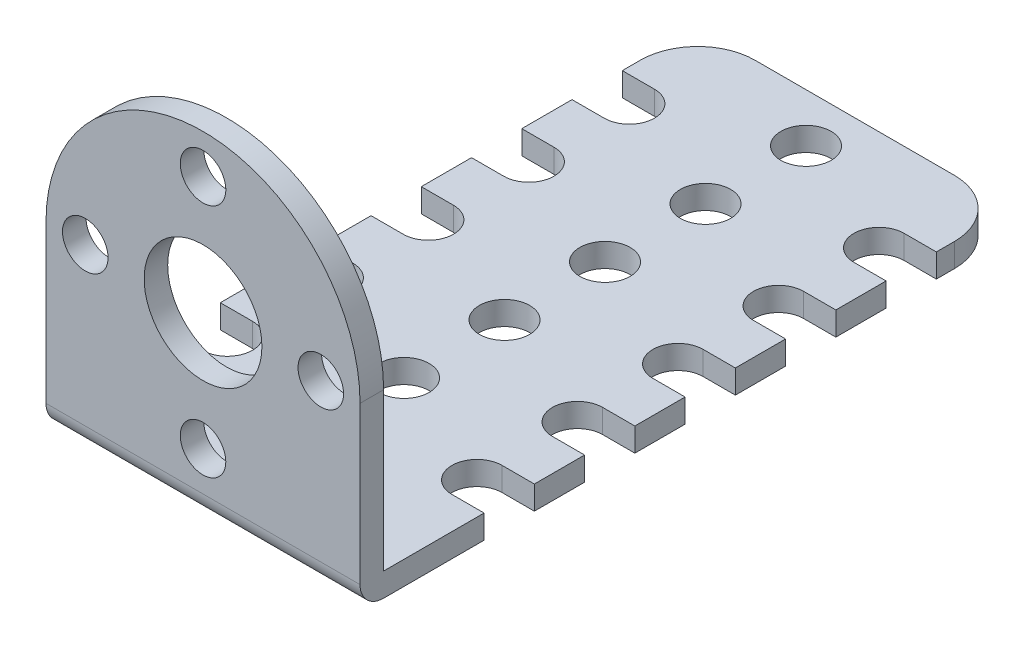
SolidWorks part; units mm, degrees
ref_plane "Front Plane" through (0, 0, 0) normal (0, 0, 1) x (1, 0, 0)
ref_plane "Top Plane" through (0, 0, 0) normal (0, 1, 0) x (1, 0, 0)
ref_plane "Right Plane" through (0, 0, 0) normal (1, 0, 0) x (0, 0, -1)
sketch "Sketch1" plane through (0, 0, 0) normal (1, 0, 0) x (0, 0, -1)
  line L0 (0, 0) -> (0, 20)
  line L1 (0, 20) -> (-1.5, 20)
  line L2 (-1.5, 20) -> (-1.5, -1.5)
  line L3 (-1.5, -1.5) -> (40, -1.5)
  line L4 (40, -1.5) -> (40, 0)
  line L5 (40, 0) -> (0, 0)
  point P3 (40, -0.75)
  dimension "D1" = 1.5
  dimension "D2" = 20
  dimension "D3" = 1.5
  dimension "D4" = 40
  dimension "D5" = 21.5
extrude "Boss-Extrude1" add sketch "Sketch1" against normal blind 20
sketch "Sketch2" plane through (0, 0, 0) normal (1, 0, 0) x (0, 0, -1)
  line L0 (-1.5, 20) -> (-1.5, -1.5) construction
  line L1 (-1.5, -1.5) -> (40, -1.5) construction
  line L2 (-1.5, 0) -> (-1.5, -1.5)
  line L3 (-1.5, -1.5) -> (0, -1.5)
  arc A0 (-1.5, 0) -> (0, -1.5) centre (0, 0) ccw
  dimension "D1" = 0
  dimension "D2" = 0
  dimension "D3" = 0
extrude "Cut-Extrude2" cut sketch "Sketch2" against normal blind 20
sketch "Sketch3" plane through (0, 0, 1.5) normal (0, 0, 1) x (1, 0, 0)
  line L0 (-20, 20) -> (-20, 0) construction
  line L1 (0, 20) -> (0, 0) construction
  line L2 (-20, 20) -> (0, 20) construction
  line L7 (-20, 10) -> (-20, 21.7905)
  line L8 (-20, 21.7905) -> (0, 21.7905)
  line L9 (0, 21.7905) -> (0, 10)
  arc A0 (-20, 10) -> (0, 10) centre (-10, 10) cw
  dimension "D3" = 0
  dimension "D1" = 0
  dimension "D2" = 11.7905
  dimension "D4" = 20
extrude "Cut-Extrude3" cut sketch "Sketch3" against normal blind 20
sketch "Sketch4" plane through (0, 0, 1.5) normal (0, 0, 1) x (1, 0, 0)
  line L0 (-20, -1.5) -> (0, -1.5) construction
  circle A0 centre (-10, 10) radius 3.75
  point P4 (-10, -1.5)
  dimension "D3" = 7.5
  dimension "D1" = 11.5
  dimension "D2" = 0
extrude "Cut-Extrude4" cut sketch "Sketch4" against normal blind 20
sketch "Sketch5" plane through (0, 0, 1.5) normal (0, 0, 1) x (1, 0, 0)
  circle A0 centre (-10, 2.5) radius 1.45
  circle A1 centre (-10, 10) radius 3.75 construction
  dimension "D2" = 2.9
  dimension "D3" = 7.5
  dimension "D1" = 0
extrude "Cut-Extrude5" cut sketch "Sketch5" against normal blind 20
pattern_circular "CirPattern1" count 4 every 90 about axis through (-10, 10, 0) along (0, 0, 1) of "Cut-Extrude5"
sketch "Sketch6" plane through (0, 0, 0) normal (0, 1, 0) x (1, 0, 0)
  line L0 (-20, -1.5) -> (0, -1.5) construction
  circle A0 centre (-10, 4.9) radius 1.6
  point P4 (-10, -1.5)
  dimension "D2" = 3.2
  dimension "D3" = 0
  dimension "D1" = 6.4
extrude "Cut-Extrude6" cut sketch "Sketch6" against normal blind 20
pattern_linear "LPattern1" count 6 spacing 6.4 along (0, 0, -1) of "Cut-Extrude6"
sketch "Sketch7" plane through (0, 0, 0) normal (0, 1, 0) x (1, 0, 0)
  line L0 (0, 6.4) -> (-2.05, 6.4)
  line L1 (0, 40) -> (0, 0) construction
  line L2 (-2.05, 9.6) -> (0, 9.6)
  line L3 (0, 9.6) -> (0, 6.4)
  line L4 (-20, -1.5) -> (0, -1.5) construction
  arc A0 (-2.05, 9.6) -> (-2.05, 6.4) centre (-2.05, 8) ccw
  point P9 (-10, -1.5)
  dimension "D1" = 1.6
  dimension "D2" = 7.95
  dimension "D3" = 9.5
extrude "Cut-Extrude7" cut sketch "Sketch7" against normal blind 20
pattern_linear "LPattern2" count 5 spacing 6.4 along (0, 0, -1) of "Cut-Extrude7"
ref_plane "Plane1" through (-10, 0, 0) normal (-1, 0, 0) x (0, 0, 1)
mirror "Mirror1" about plane through (-10, 0, 0) normal (-1, 0, 0) of "LPattern2", "Cut-Extrude7"
fillet "Fillet3" radius 3.65 1 edges at (0, -0.75, -40)
fillet "Fillet4" radius 3.65 1 edges at (-20, -0.75, -40)
